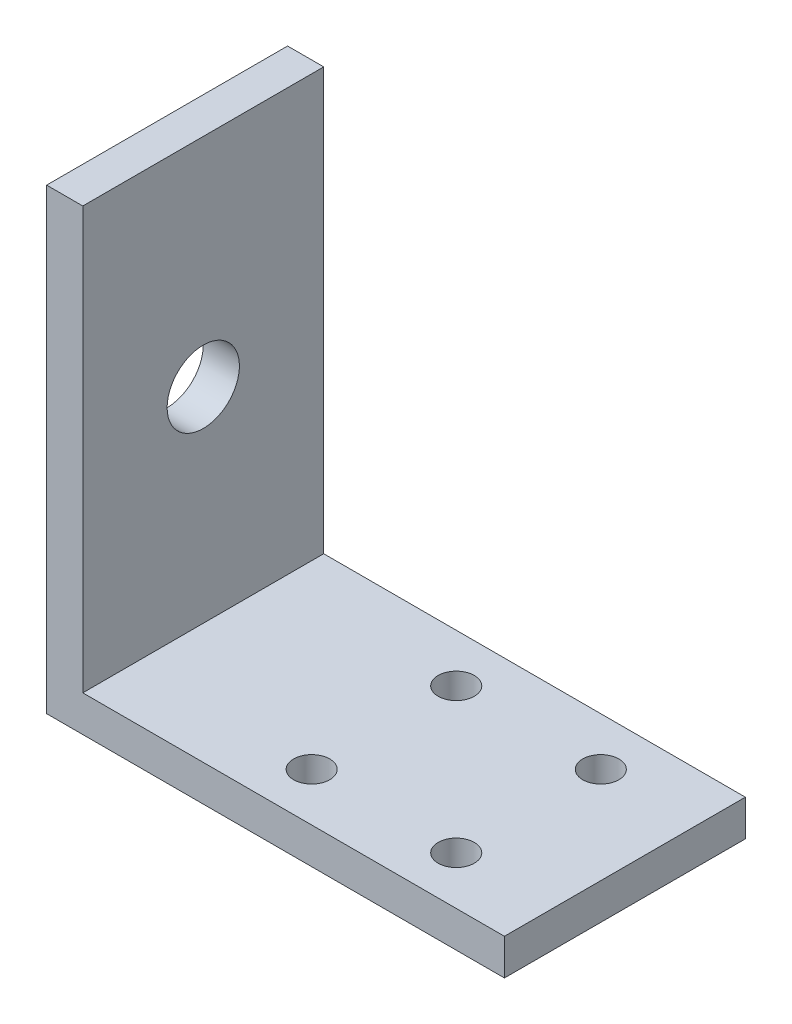
SolidWorks part; units mm, degrees
material "6063-O"
ref_plane "Front" through (0, 0, 0) normal (0, 0, 1) x (1, 0, 0)
ref_plane "Top" through (0, 0, 0) normal (0, 1, 0) x (1, 0, 0)
ref_plane "Right" through (0, 0, 0) normal (1, 0, 0) x (0, 0, -1)
sketch "草图1" plane through (0, 0, 0) normal (0, 0, 1) x (1, 0, 0)
  line L0 (0, 0) -> (0, 38)
  line L1 (0, 38) -> (3, 38)
  line L2 (3, 38) -> (3, 3)
  line L3 (3, 3) -> (38, 3)
  line L4 (38, 3) -> (38, 0)
  line L5 (38, 0) -> (0, 0)
  dimension "D1" = 38
  dimension "D2" = 3
  dimension "D3" = 35
  dimension "D4" = 35
extrude "凸台-拉伸1" add sketch "草图1" along normal blind 20
sketch "草图2" plane through (0, 0, 0) normal (-1, 0, 0) x (0, 0, 1)
  line L0 (10, 38) -> (10, 0) construction
  line L1 (20, 38) -> (0, 38) construction
  line L2 (20, 0) -> (0, 0) construction
  circle A0 centre (10, 20) radius 3
  dimension "D1" = 6
  dimension "D2" = 20
extrude "切除-拉伸1" cut sketch "草图2" against normal through all
sketch "草图3" plane through (0, 3, 0) normal (0, 1, 0) x (1, 0, 0)
  line L0 (0, -10) -> (38.1615, -10) construction
  line L1 (0, -20) -> (0, 0) construction
  circle A0 centre (18, -4) radius 1.5
  circle A1 centre (18, -16) radius 1.5
  circle A2 centre (30, -4) radius 1.5
  circle A3 centre (30, -16) radius 1.5
  dimension "D1" = 3
  dimension "D2" = 3
  dimension "D3" = 12
  dimension "D4" = 18
  dimension "D5" = 2
extrude "切除-拉伸2" cut sketch "草图3" against normal through all
